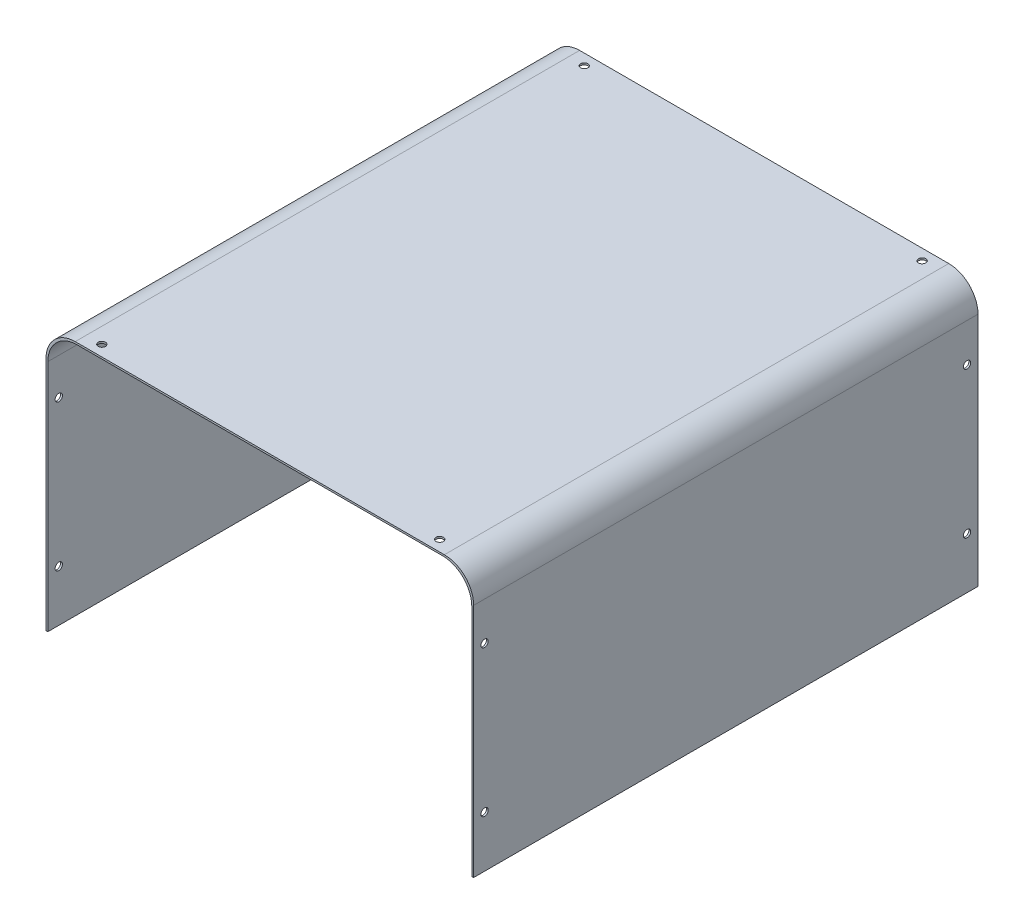
SolidWorks part; units mm, degrees
ref_plane "Спереди" through (0, 0, 0) normal (0, 0, 1) x (1, 0, 0)
ref_plane "Сверху" through (0, 0, 0) normal (0, 1, 0) x (1, 0, 0)
ref_plane "Справа" through (0, 0, 0) normal (1, 0, 0) x (0, 0, -1)
sketch "Эскиз1" plane through (0, 0, 0) normal (0, 1, 0) x (1, 0, 0)
  line L1 (-25.2657, 65.766) -> (91.7343, 65.766)
  line L2 (-25.2657, 65.766) -> (-25.2657, -72.234)
  line L3 (-25.2657, -72.234) -> (91.7343, -72.234)
  line L4 (91.7343, 65.766) -> (91.7343, -72.234)
extrude "Бобышка-Вытянуть1" add sketch "Эскиз1" along normal blind 72.5 contours L2 L1 L4 L3
sketch "Эскиз2" plane through (0, 0, -65.766) normal (0, 0, -1) x (-1, 0, 0)
  line L0 (-91.7343, 64.5) -> (-91.7343, 72.5)
  line L5 (-91.7343, 72.5) -> (-83.7343, 72.5)
  line L6 (17.2657, 72.5) -> (25.2657, 72.5)
  line L7 (25.2657, 72.5) -> (25.2657, 64.5)
  arc A0 (17.2657, 72.5) -> (25.2657, 64.5) centre (17.2657, 64.5) cw
  arc A1 (-83.7343, 72.5) -> (-91.7343, 64.5) centre (-83.7343, 64.5) ccw
  point P10 (-91.7343, 72.5)
  dimension "D1" = 8
extrude "Вырез-Вытянуть1" cut sketch "Эскиз2" against normal blind 140
sketch "Эскиз3" plane through (0, 0, 72.234) normal (0, 0, 1) x (1, 0, 0)
  line L17 (-24.7657, 0) -> (91.2343, 0)
  line L18 (-24.7657, 0) -> (-24.7657, 64)
  line L19 (-16.7657, 72) -> (83.2343, 72)
  line L20 (91.2343, 0) -> (91.2343, 64)
  arc A0 (83.2343, 72) -> (91.2343, 64) centre (83.2343, 64) cw
  arc A1 (-24.7657, 64) -> (-16.7657, 72) centre (-16.7657, 64) cw
  dimension "D1" = 8
extrude "Вырез-Вытянуть2" cut sketch "Эскиз3" against normal blind 140
sketch "Эскиз6" plane through (-25.2657, 0, 0) normal (-1, 0, 0) x (0, 0, 1)
  circle A0 centre (-62.766, 14) radius 1
  circle A2 centre (69.234, 14) radius 1
  circle A4 centre (-62.766, 54) radius 1
  circle A5 centre (69.234, 54) radius 1
extrude "Вырез-Вытянуть5" cut sketch "Эскиз6" against normal blind 140
sketch "Эскиз7" plane through (0, 72, 0) normal (0, -1, 0) x (-1, 0, 0)
  circle A1 centre (-79.4543, 62.766) radius 1
  circle A2 centre (-582.9047, 16.1427) radius 1
  circle A3 centre (12.9857, -69.234) radius 1
  circle A4 centre (-79.4543, -69.234) radius 1
  circle A5 centre (12.9857, 62.766) radius 1
extrude "Вырез-Вытянуть7" cut sketch "Эскиз7" against normal blind 140
